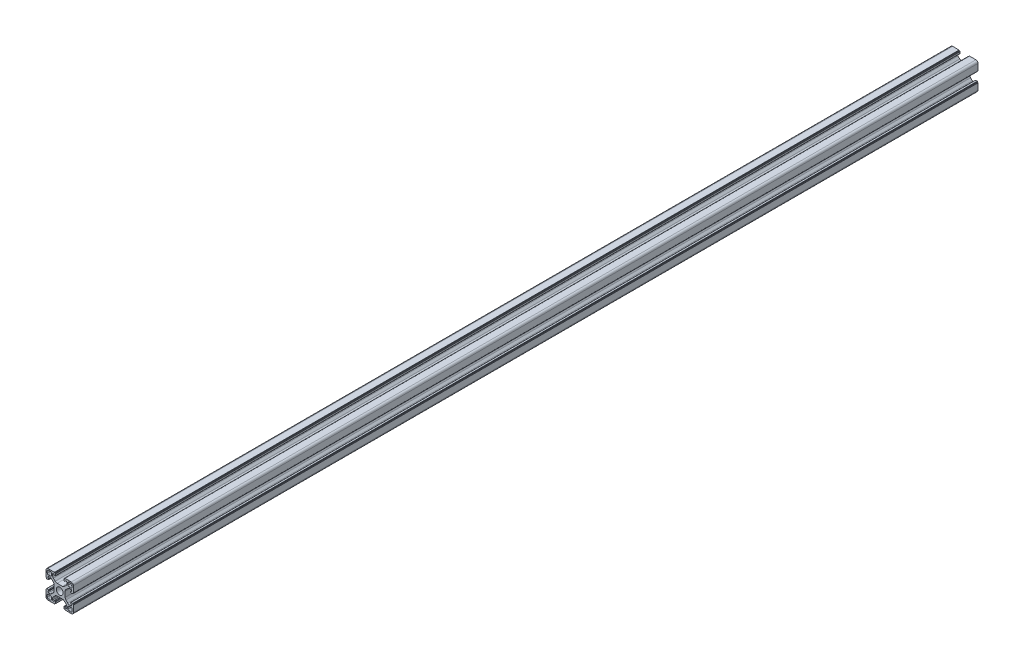
SolidWorks part; units mm, degrees
ref_plane "Спереди" through (0, 0, 0) normal (0, 0, 1) x (1, 0, 0)
ref_plane "Сверху" through (0, 0, 0) normal (0, 1, 0) x (1, 0, 0)
ref_plane "Справа" through (0, 0, 0) normal (1, 0, 0) x (0, 0, -1)
sketch "Эскиз1" plane through (0, 0, 0) normal (0, 0, 1) x (1, 0, 0)
  line L0 (-9.367, 48.5619) -> (-12.367, 45.5619) construction
  line L1 (-18.467, 43.4619) -> (-16.5682, 43.4619)
  line L2 (-18.467, 39.4619) -> (-8.467, 49.4619) construction
  line L3 (-10.867, 47.0619) -> (-12.367, 48.5619) construction
  line L4 (-15.154, 44.0477) -> (-13.8528, 45.3489)
  line L5 (-11.567, 45.5619) -> (-10.167, 45.5619)
  line L6 (-12.367, 46.3619) -> (-12.367, 47.7619)
  line L7 (-10.167, 48.5619) -> (-11.567, 48.5619)
  line L8 (-13.267, 47.6619) -> (-13.267, 46.7631)
  line L9 (-14.7038, 47.5351) -> (-14.2234, 48.0154)
  line L10 (-15.267, 49.0109) -> (-14.767, 49.0109)
  line L11 (-14.8805, 47.4619) -> (-15.167, 47.4619)
  line L12 (-13.8699, 48.1619) -> (-13.767, 48.1619)
  line L13 (-14.767, 49.3119) -> (-14.767, 49.0109)
  line L14 (-15.417, 48.8609) -> (-15.417, 47.7119)
  line L15 (-9.967, 49.4619) -> (-14.617, 49.4619)
  line L16 (-9.367, 47.7619) -> (-9.367, 46.3619)
  line L17 (-8.467, 47.9619) -> (-8.467, 43.3119)
  line L18 (-9.0679, 42.5119) -> (-10.217, 42.5119)
  line L19 (-8.617, 43.1619) -> (-8.9179, 43.1619)
  line L20 (-9.767, 44.059) -> (-9.767, 44.1619)
  line L21 (-10.467, 43.0483) -> (-10.467, 42.7619)
  line L22 (-8.9179, 42.6619) -> (-8.9179, 43.1619)
  line L23 (-10.3938, 43.2251) -> (-9.9134, 43.7054)
  line L24 (-10.267, 44.6619) -> (-11.1658, 44.6619)
  line L25 (-13.8812, 42.7749) -> (-12.58, 44.0761)
  line L26 (-14.467, 39.4619) -> (-14.467, 41.3607)
  line L27 (-14.467, 39.4619) -> (-14.467, 37.5631)
  line L28 (-13.8812, 36.1489) -> (-12.58, 34.8477)
  line L29 (-12.367, 32.5619) -> (-12.367, 31.1619)
  line L30 (-11.567, 33.3619) -> (-10.167, 33.3619)
  line L31 (-9.367, 31.1619) -> (-9.367, 32.5619)
  line L32 (-10.267, 34.2619) -> (-11.1658, 34.2619)
  line L33 (-10.3938, 35.6987) -> (-9.9134, 35.2183)
  line L34 (-8.9179, 36.2619) -> (-8.9179, 35.7619)
  line L35 (-10.467, 35.8754) -> (-10.467, 36.1619)
  line L36 (-9.767, 34.8648) -> (-9.767, 34.7619)
  line L37 (-8.617, 35.7619) -> (-8.9179, 35.7619)
  line L38 (-9.0679, 36.4119) -> (-10.217, 36.4119)
  line L39 (-8.467, 30.9619) -> (-8.467, 35.6119)
  line L40 (-10.167, 30.3619) -> (-11.567, 30.3619)
  line L41 (-9.967, 29.4619) -> (-14.617, 29.4619)
  line L42 (-15.417, 30.0628) -> (-15.417, 31.2119)
  line L43 (-14.767, 29.6119) -> (-14.767, 29.9128)
  line L44 (-13.8699, 30.7619) -> (-13.767, 30.7619)
  line L45 (-14.8805, 31.4619) -> (-15.167, 31.4619)
  line L46 (-15.267, 29.9128) -> (-14.767, 29.9128)
  line L47 (-14.7038, 31.3887) -> (-14.2234, 30.9083)
  line L48 (-13.267, 31.2619) -> (-13.267, 32.1607)
  line L49 (-15.154, 34.8761) -> (-13.8528, 33.5749)
  line L50 (-18.467, 35.4619) -> (-16.5682, 35.4619)
  line L51 (-9.367, 30.3619) -> (-12.367, 33.3619) construction
  line L52 (-18.467, 39.4619) -> (-8.467, 29.4619) construction
  line L53 (-10.867, 31.8619) -> (-9.367, 33.3619) construction
  line L54 (-18.467, 35.4619) -> (-20.3658, 35.4619)
  line L55 (-21.78, 34.8761) -> (-23.0812, 33.5749)
  line L56 (-25.367, 33.3619) -> (-26.767, 33.3619)
  line L57 (-24.567, 32.5619) -> (-24.567, 31.1619)
  line L58 (-26.767, 30.3619) -> (-25.367, 30.3619)
  line L59 (-23.667, 31.2619) -> (-23.667, 32.1607)
  line L60 (-22.2302, 31.3887) -> (-22.7105, 30.9083)
  line L61 (-21.667, 29.9128) -> (-22.167, 29.9128)
  line L62 (-22.0534, 31.4619) -> (-21.767, 31.4619)
  line L63 (-23.0641, 30.7619) -> (-23.167, 30.7619)
  line L64 (-22.167, 29.6119) -> (-22.167, 29.9128)
  line L65 (-21.517, 30.0628) -> (-21.517, 31.2119)
  line L66 (-26.967, 29.4619) -> (-22.317, 29.4619)
  line L67 (-27.567, 31.1619) -> (-27.567, 32.5619)
  line L68 (-28.467, 30.9619) -> (-28.467, 35.6119)
  line L69 (-27.8661, 36.4119) -> (-26.717, 36.4119)
  line L70 (-28.317, 35.7619) -> (-28.0161, 35.7619)
  line L71 (-27.167, 34.8648) -> (-27.167, 34.7619)
  line L72 (-26.467, 35.8754) -> (-26.467, 36.1619)
  line L73 (-28.0161, 36.2619) -> (-28.0161, 35.7619)
  line L74 (-26.5402, 35.6987) -> (-27.0205, 35.2183)
  line L75 (-26.667, 34.2619) -> (-25.7682, 34.2619)
  line L76 (-23.0528, 36.1489) -> (-24.354, 34.8477)
  line L77 (-22.467, 39.4619) -> (-22.467, 37.5631)
  line L78 (-27.567, 30.3619) -> (-24.567, 33.3619) construction
  line L79 (-18.467, 39.4619) -> (-28.467, 29.4619) construction
  line L80 (-26.067, 31.8619) -> (-24.567, 30.3619) construction
  line L81 (-22.467, 39.4619) -> (-22.467, 41.3607)
  line L82 (-23.0528, 42.7749) -> (-24.354, 44.0761)
  line L83 (-24.567, 46.3619) -> (-24.567, 47.7619)
  line L84 (-25.367, 45.5619) -> (-26.767, 45.5619)
  line L85 (-27.567, 47.7619) -> (-27.567, 46.3619)
  line L86 (-26.667, 44.6619) -> (-25.7682, 44.6619)
  line L87 (-26.5402, 43.2251) -> (-27.0205, 43.7054)
  line L88 (-28.0161, 42.6619) -> (-28.0161, 43.1619)
  line L89 (-26.467, 43.0483) -> (-26.467, 42.7619)
  line L90 (-27.167, 44.059) -> (-27.167, 44.1619)
  line L91 (-28.317, 43.1619) -> (-28.0161, 43.1619)
  line L92 (-27.8661, 42.5119) -> (-26.717, 42.5119)
  line L93 (-28.467, 47.9619) -> (-28.467, 43.3119)
  line L94 (-26.767, 48.5619) -> (-25.367, 48.5619)
  line L95 (-26.967, 49.4619) -> (-22.317, 49.4619)
  line L96 (-21.517, 48.8609) -> (-21.517, 47.7119)
  line L97 (-22.167, 49.3119) -> (-22.167, 49.0109)
  line L98 (-23.0641, 48.1619) -> (-23.167, 48.1619)
  line L99 (-22.0534, 47.4619) -> (-21.767, 47.4619)
  line L100 (-21.667, 49.0109) -> (-22.167, 49.0109)
  line L101 (-22.2302, 47.5351) -> (-22.7105, 48.0154)
  line L102 (-23.667, 47.6619) -> (-23.667, 46.7631)
  line L103 (-21.78, 44.0477) -> (-23.0812, 45.3489)
  line L104 (-18.467, 43.4619) -> (-20.3658, 43.4619)
  line L105 (-30.231, 39.4619) -> (-6.9626, 39.4619) construction
  line L106 (-27.567, 48.5619) -> (-24.567, 45.5619) construction
  line L107 (-18.467, 27.3755) -> (-18.467, 50.1808) construction
  line L108 (-18.467, 39.4619) -> (-28.467, 49.4619) construction
  line L109 (-26.067, 47.0619) -> (-27.567, 45.5619) construction
  arc A0 (-9.367, 47.7619) -> (-10.167, 48.5619) centre (-10.167, 47.7619) ccw
  arc A1 (-11.567, 48.5619) -> (-12.367, 47.7619) centre (-11.567, 47.7619) ccw
  arc A2 (-11.567, 45.5619) -> (-12.367, 46.3619) centre (-11.567, 46.3619) cw
  arc A3 (-9.967, 49.4619) -> (-8.467, 47.9619) centre (-9.967, 47.9619) cw
  arc A4 (-15.267, 49.0109) -> (-15.417, 48.8609) centre (-15.267, 48.8609) ccw
  arc A5 (-14.617, 49.4619) -> (-14.767, 49.3119) centre (-14.617, 49.3119) ccw
  arc A6 (-14.8805, 47.4619) -> (-14.7038, 47.5351) centre (-14.8805, 47.7119) ccw
  arc A7 (-15.167, 47.4619) -> (-15.417, 47.7119) centre (-15.167, 47.7119) cw
  arc A8 (-14.2234, 48.0154) -> (-13.8699, 48.1619) centre (-13.8699, 47.6619) cw
  arc A9 (-13.767, 48.1619) -> (-13.267, 47.6619) centre (-13.767, 47.6619) cw
  arc A10 (-15.967, 39.4619) -> (-18.467, 41.9619) centre (-18.467, 39.4619) ccw
  arc A11 (-16.5682, 43.4619) -> (-15.154, 44.0477) centre (-16.5682, 45.4619) ccw
  arc A12 (-13.267, 46.7631) -> (-13.8528, 45.3489) centre (-15.267, 46.7631) cw
  arc A13 (-9.367, 46.3619) -> (-10.167, 45.5619) centre (-10.167, 46.3619) cw
  arc A14 (-9.767, 44.1619) -> (-10.267, 44.6619) centre (-10.267, 44.1619) ccw
  arc A15 (-9.9134, 43.7054) -> (-9.767, 44.059) centre (-10.267, 44.059) ccw
  arc A16 (-10.467, 42.7619) -> (-10.217, 42.5119) centre (-10.217, 42.7619) ccw
  arc A17 (-10.467, 43.0483) -> (-10.3938, 43.2251) centre (-10.217, 43.0483) cw
  arc A18 (-8.467, 43.3119) -> (-8.617, 43.1619) centre (-8.617, 43.3119) cw
  arc A19 (-8.9179, 42.6619) -> (-9.0679, 42.5119) centre (-9.0679, 42.6619) cw
  arc A20 (-11.1658, 44.6619) -> (-12.58, 44.0761) centre (-11.1658, 42.6619) ccw
  arc A21 (-14.467, 41.3607) -> (-13.8812, 42.7749) centre (-12.467, 41.3607) cw
  arc A22 (-10.167, 30.3619) -> (-9.367, 31.1619) centre (-10.167, 31.1619) ccw
  arc A23 (-9.367, 32.5619) -> (-10.167, 33.3619) centre (-10.167, 32.5619) ccw
  arc A24 (-12.367, 32.5619) -> (-11.567, 33.3619) centre (-11.567, 32.5619) cw
  arc A25 (-8.467, 30.9619) -> (-9.967, 29.4619) centre (-9.967, 30.9619) cw
  arc A26 (-8.9179, 36.2619) -> (-9.0679, 36.4119) centre (-9.0679, 36.2619) ccw
  arc A27 (-8.467, 35.6119) -> (-8.617, 35.7619) centre (-8.617, 35.6119) ccw
  arc A28 (-10.467, 35.8754) -> (-10.3938, 35.6987) centre (-10.217, 35.8754) ccw
  arc A29 (-10.467, 36.1619) -> (-10.217, 36.4119) centre (-10.217, 36.1619) cw
  arc A30 (-9.9134, 35.2183) -> (-9.767, 34.8648) centre (-10.267, 34.8648) cw
  arc A31 (-9.767, 34.7619) -> (-10.267, 34.2619) centre (-10.267, 34.7619) cw
  arc A32 (-18.467, 36.9619) -> (-15.967, 39.4619) centre (-18.467, 39.4619) ccw
  arc A33 (-14.467, 37.5631) -> (-13.8812, 36.1489) centre (-12.467, 37.5631) ccw
  arc A34 (-11.1658, 34.2619) -> (-12.58, 34.8477) centre (-11.1658, 36.2619) cw
  arc A35 (-11.567, 30.3619) -> (-12.367, 31.1619) centre (-11.567, 31.1619) cw
  arc A36 (-13.767, 30.7619) -> (-13.267, 31.2619) centre (-13.767, 31.2619) ccw
  arc A37 (-14.2234, 30.9083) -> (-13.8699, 30.7619) centre (-13.8699, 31.2619) ccw
  arc A38 (-15.167, 31.4619) -> (-15.417, 31.2119) centre (-15.167, 31.2119) ccw
  arc A39 (-14.8805, 31.4619) -> (-14.7038, 31.3887) centre (-14.8805, 31.2119) cw
  arc A40 (-14.617, 29.4619) -> (-14.767, 29.6119) centre (-14.617, 29.6119) cw
  arc A41 (-15.267, 29.9128) -> (-15.417, 30.0628) centre (-15.267, 30.0628) cw
  arc A42 (-13.267, 32.1607) -> (-13.8528, 33.5749) centre (-15.267, 32.1607) ccw
  arc A43 (-16.5682, 35.4619) -> (-15.154, 34.8761) centre (-16.5682, 33.4619) cw
  arc A44 (-27.567, 31.1619) -> (-26.767, 30.3619) centre (-26.767, 31.1619) ccw
  arc A45 (-25.367, 30.3619) -> (-24.567, 31.1619) centre (-25.367, 31.1619) ccw
  arc A46 (-25.367, 33.3619) -> (-24.567, 32.5619) centre (-25.367, 32.5619) cw
  arc A47 (-26.967, 29.4619) -> (-28.467, 30.9619) centre (-26.967, 30.9619) cw
  arc A48 (-21.667, 29.9128) -> (-21.517, 30.0628) centre (-21.667, 30.0628) ccw
  arc A49 (-22.317, 29.4619) -> (-22.167, 29.6119) centre (-22.317, 29.6119) ccw
  arc A50 (-22.0534, 31.4619) -> (-22.2302, 31.3887) centre (-22.0534, 31.2119) ccw
  arc A51 (-21.767, 31.4619) -> (-21.517, 31.2119) centre (-21.767, 31.2119) cw
  arc A52 (-22.7105, 30.9083) -> (-23.0641, 30.7619) centre (-23.0641, 31.2619) cw
  arc A53 (-23.167, 30.7619) -> (-23.667, 31.2619) centre (-23.167, 31.2619) cw
  arc A54 (-20.967, 39.4619) -> (-18.467, 36.9619) centre (-18.467, 39.4619) ccw
  arc A55 (-20.3658, 35.4619) -> (-21.78, 34.8761) centre (-20.3658, 33.4619) ccw
  arc A56 (-23.667, 32.1607) -> (-23.0812, 33.5749) centre (-21.667, 32.1607) cw
  arc A57 (-27.567, 32.5619) -> (-26.767, 33.3619) centre (-26.767, 32.5619) cw
  arc A58 (-27.167, 34.7619) -> (-26.667, 34.2619) centre (-26.667, 34.7619) ccw
  arc A59 (-27.0205, 35.2183) -> (-27.167, 34.8648) centre (-26.667, 34.8648) ccw
  arc A60 (-26.467, 36.1619) -> (-26.717, 36.4119) centre (-26.717, 36.1619) ccw
  arc A61 (-26.467, 35.8754) -> (-26.5402, 35.6987) centre (-26.717, 35.8754) cw
  arc A62 (-28.467, 35.6119) -> (-28.317, 35.7619) centre (-28.317, 35.6119) cw
  arc A63 (-28.0161, 36.2619) -> (-27.8661, 36.4119) centre (-27.8661, 36.2619) cw
  arc A64 (-25.7682, 34.2619) -> (-24.354, 34.8477) centre (-25.7682, 36.2619) ccw
  arc A65 (-22.467, 37.5631) -> (-23.0528, 36.1489) centre (-24.467, 37.5631) cw
  arc A66 (-26.767, 48.5619) -> (-27.567, 47.7619) centre (-26.767, 47.7619) ccw
  arc A67 (-27.567, 46.3619) -> (-26.767, 45.5619) centre (-26.767, 46.3619) ccw
  arc A68 (-24.567, 46.3619) -> (-25.367, 45.5619) centre (-25.367, 46.3619) cw
  arc A69 (-28.467, 47.9619) -> (-26.967, 49.4619) centre (-26.967, 47.9619) cw
  arc A70 (-28.0161, 42.6619) -> (-27.8661, 42.5119) centre (-27.8661, 42.6619) ccw
  arc A71 (-28.467, 43.3119) -> (-28.317, 43.1619) centre (-28.317, 43.3119) ccw
  arc A72 (-26.467, 43.0483) -> (-26.5402, 43.2251) centre (-26.717, 43.0483) ccw
  arc A73 (-26.467, 42.7619) -> (-26.717, 42.5119) centre (-26.717, 42.7619) cw
  arc A74 (-27.0205, 43.7054) -> (-27.167, 44.059) centre (-26.667, 44.059) cw
  arc A75 (-27.167, 44.1619) -> (-26.667, 44.6619) centre (-26.667, 44.1619) cw
  arc A76 (-18.467, 41.9619) -> (-20.967, 39.4619) centre (-18.467, 39.4619) ccw
  arc A77 (-22.467, 41.3607) -> (-23.0528, 42.7749) centre (-24.467, 41.3607) ccw
  arc A78 (-25.7682, 44.6619) -> (-24.354, 44.0761) centre (-25.7682, 42.6619) cw
  arc A79 (-25.367, 48.5619) -> (-24.567, 47.7619) centre (-25.367, 47.7619) cw
  arc A80 (-23.167, 48.1619) -> (-23.667, 47.6619) centre (-23.167, 47.6619) ccw
  arc A81 (-22.7105, 48.0154) -> (-23.0641, 48.1619) centre (-23.0641, 47.6619) ccw
  arc A82 (-21.767, 47.4619) -> (-21.517, 47.7119) centre (-21.767, 47.7119) ccw
  arc A83 (-22.0534, 47.4619) -> (-22.2302, 47.5351) centre (-22.0534, 47.7119) cw
  arc A84 (-22.317, 49.4619) -> (-22.167, 49.3119) centre (-22.317, 49.3119) cw
  arc A85 (-21.667, 49.0109) -> (-21.517, 48.8609) centre (-21.667, 48.8609) cw
  arc A86 (-23.667, 46.7631) -> (-23.0812, 45.3489) centre (-21.667, 46.7631) ccw
  arc A87 (-20.3658, 43.4619) -> (-21.78, 44.0477) centre (-20.3658, 45.4619) cw
  point P0 (-18.467, 39.4619)
  point P9 (-18.467, 39.4619)
  point P40 (-9.767, 43.1619)
  point P93 (-14.767, 30.7619)
  point P144 (-14.767, 48.1619)
  point P152 (-9.767, 35.7619)
  point P153 (-18.467, 35.5376)
  point P154 (-18.467, 39.4619)
  point P189 (-27.167, 35.7619)
  point P228 (-22.167, 30.7619)
  point P229 (-22.3912, 39.4619)
  point P230 (-18.467, 39.4619)
  point P268 (-22.167, 48.1619)
  point P273 (-14.5427, 39.4619)
  point P306 (-27.167, 43.1619)
  point P307 (-18.467, 43.3861)
  point P309 (-18.467, 39.4619)
  dimension "D3" = 5
  dimension "D6" = 2
  dimension "D1" = 2
  dimension "D2" = 6
  dimension "D4" = 4
  dimension "D5" = 0.9
extrude "Бобышка-Вытянуть1" add sketch "Эскиз1" along normal blind 660
